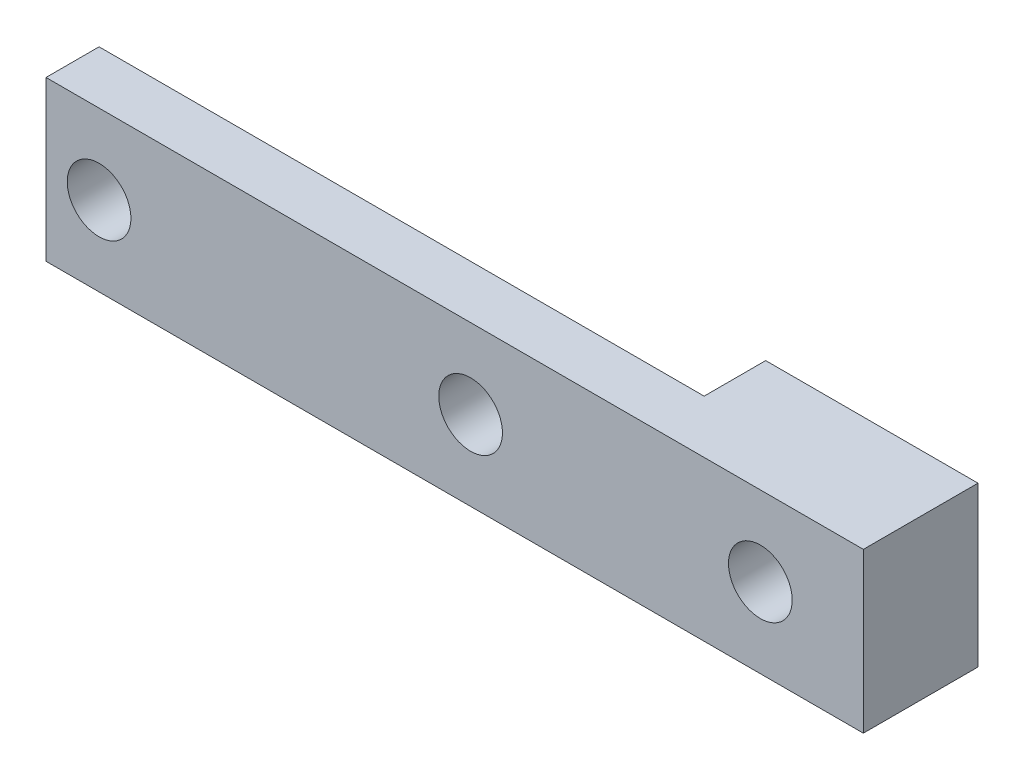
SolidWorks part; units mm, degrees
ref_plane "Front Plane" through (0, 0, 0) normal (1, 0, 0) x (0, 1, 0)
ref_plane "Top Plane" through (0, 0, 0) normal (0, 0, 1) x (0, 1, 0)
ref_plane "Right Plane" through (0, 0, 0) normal (0, 1, 0) x (-1, 0, 0)
sketch "Sketch1" plane through (0, 0, 0) normal (0, 0, 1) x (0, 1, 0)
  line L0 (0, 19.25) -> (0, -19.25) construction
  line L1 (-3.75, -19.25) -> (3.75, -19.25)
  line L2 (-3.75, -19.25) -> (-3.75, 19.25)
  line L3 (-3.75, 19.25) -> (3.75, 19.25)
  line L4 (3.75, -19.25) -> (3.75, 19.25)
  circle A0 centre (0, 16.75) radius 1.5
  circle A1 centre (0, -0.75) radius 1.5
  circle A2 centre (0, -14.398) radius 1.5
  point P0 (0, 0)
  point P12 (0, 0)
  dimension "D3" = 3
  dimension "D4" = 3
  dimension "D6" = 3
  dimension "D1" = 38.5
  dimension "D2" = 7.5
  dimension "D5" = 17.5
  dimension "D7" = 2.5
  dimension "D8" = 13.648
extrude "Boss-Extrude1" add sketch "Sketch1" along normal blind 2.5 contours L0 L3 L2 L1 A2 A1 A0 | L3 L0 A0 A1 A2 L1 L4
sketch "Sketch2" plane through (0, 0, 0) normal (0, 0, -1) x (1, 0, 0)
  line L0 (9.25, 3.75) -> (9.25, -3.75)
  line L1 (19.25, 3.75) -> (-19.25, 3.75) construction
  line L2 (19.25, -3.75) -> (-19.25, -3.75) construction
  line L3 (19.25, 3.75) -> (19.25, -3.75) construction
  line L4 (9.25, 3.75) -> (19.25, 3.75)
  line L5 (19.25, 3.75) -> (19.25, -3.75)
  line L6 (19.25, -3.75) -> (9.25, -3.75)
  circle A0 centre (14.398, 0) radius 1.5
  dimension "D1" = 10
extrude "Boss-Extrude2" add sketch "Sketch2" along normal blind 2.9
